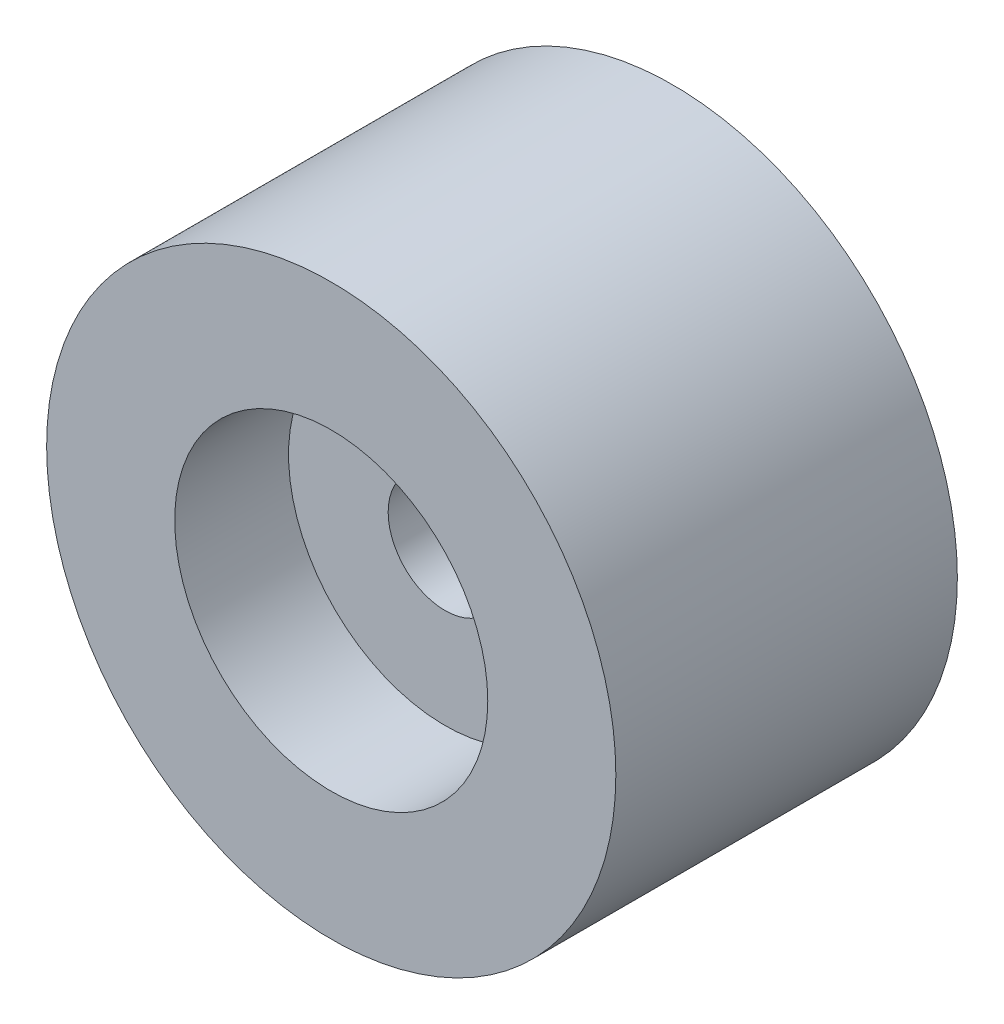
SolidWorks part; units mm, degrees
ref_plane "Front Plane" through (0, 0, 0) normal (0, 0, 1) x (1, 0, 0)
ref_plane "Top Plane" through (0, 0, 0) normal (0, 1, 0) x (1, 0, 0)
ref_plane "Right Plane" through (0, 0, 0) normal (1, 0, 0) x (0, 0, -1)
sketch "Sketch1" plane through (0, 0, 0) normal (0, 0, 1) x (1, 0, 0)
  circle A0 centre (0, 0) radius 20
  circle A1 centre (0, 0) radius 4
  dimension "D1" = 40
  dimension "D2" = 8
extrude "Extrude1" add sketch "Sketch1" along normal blind 24
sketch "Sketch2" plane through (0, 0, 24) normal (0, 0, 1) x (1, 0, 0)
  circle A0 centre (0, 0) radius 11
  dimension "D1" = 22
extrude "Cut-Extrude1" cut sketch "Sketch2" against normal blind 8
sketch "Sketch3" plane through (0, 0, 0) normal (0, 0, -1) x (-1, 0, 0)
  circle A0 centre (0, 0) radius 11
  dimension "D1" = 22
extrude "Cut-Extrude2" cut sketch "Sketch3" against normal blind 8
